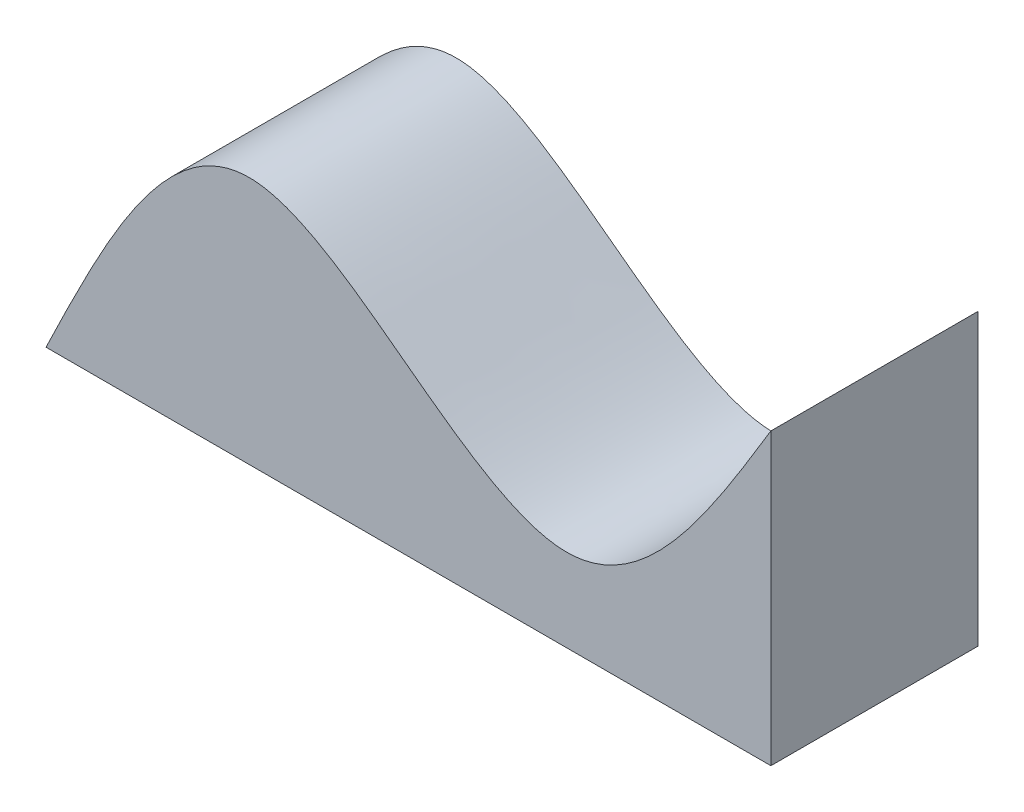
SolidWorks part; units mm, degrees
ref_plane "Front Plane" through (0, 0, 0) normal (0, 0, 1) x (1, 0, 0)
ref_plane "Top Plane" through (0, 0, 0) normal (0, 1, 0) x (1, 0, 0)
ref_plane "Right Plane" through (0, 0, 0) normal (1, 0, 0) x (0, 0, -1)
sketch "Sketch1" plane through (0, 0, 0) normal (0, 0, 1) x (1, 0, 0)
  line L0 (35, 14) -> (35, 0)
  line L1 (35, 0) -> (0, 0)
  spline S0 degree 3 poles (0, 0) (2.9441, 6.094) (9.0924, 18.8203) (25.2059, -2.2101) (31.9413, 8.9376) (35, 14) knots 0 0 0 0 0.334038 0.697576 1 1 1 1
extrude "Boss-Extrude1" add sketch "Sketch1" along normal blind 10
